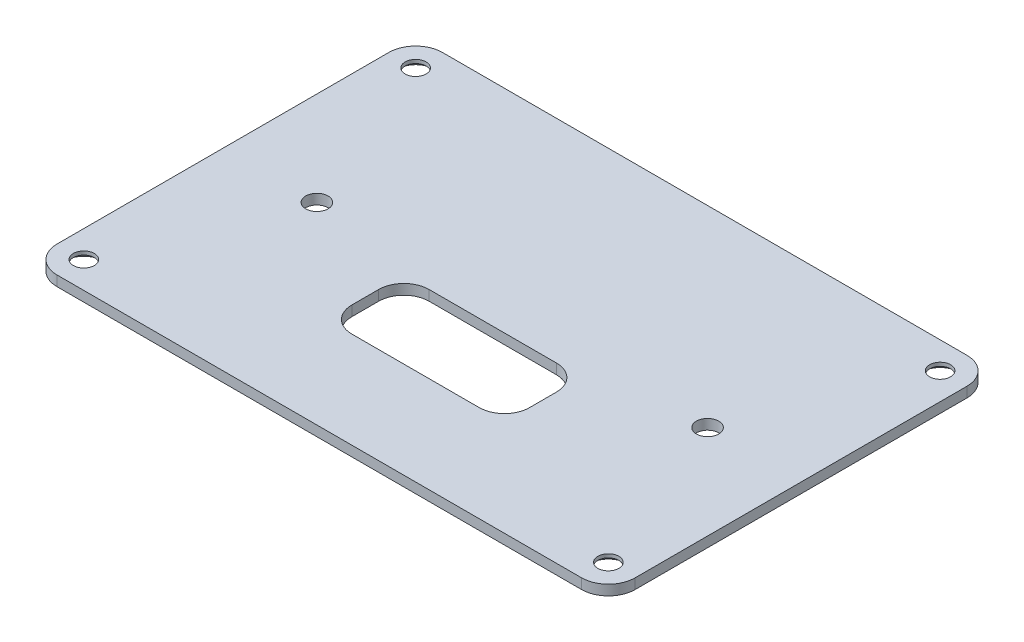
SolidWorks part; units mm, degrees
material "Plain Carbon Steel"
ref_plane "Front" through (0, 0, 0) normal (0, 0, 1) x (1, 0, 0)
ref_plane "Top" through (0, 0, 0) normal (0, 1, 0) x (1, 0, 0)
ref_plane "Right" through (0, 0, 0) normal (1, 0, 0) x (0, 0, -1)
sketch "Sketch1" plane through (0, 0, 0) normal (0, 1, 0) x (1, 0, 0)
  line L0 (-45, 0) -> (45, 0) construction
  line L1 (-45, 30) -> (45, 30) construction
  line L2 (-45, 30) -> (-45, -30) construction
  line L3 (-45, -30) -> (45, -30) construction
  line L4 (45, 30) -> (45, -30) construction
  line L5 (0, -30) -> (0, 30) construction
  line L6 (41.825, 26.825) -> (41.825, -26.825) construction
  line L7 (-41.825, -26.825) -> (41.825, -26.825) construction
  line L8 (-41.825, 26.825) -> (-41.825, -26.825) construction
  line L9 (-41.825, 26.825) -> (41.825, 26.825) construction
  line L10 (40.825, 25.825) -> (40.825, -25.825) construction
  line L11 (-40.825, -25.825) -> (40.825, -25.825) construction
  line L12 (-40.825, 25.825) -> (-40.825, -25.825) construction
  line L13 (-40.825, 25.825) -> (40.825, 25.825) construction
  line L14 (40.825, 21.65) -> (45, 21.65) construction
  line L15 (40.825, -21.65) -> (45, -21.65) construction
  line L16 (36.65, -25.825) -> (36.65, -30) construction
  line L17 (-36.65, -25.825) -> (-36.65, -30) construction
  line L18 (-40.825, -21.65) -> (-45, -21.65) construction
  line L19 (-36.65, 25.825) -> (-36.65, 30) construction
  line L20 (-40.825, 21.65) -> (-45, 21.65) construction
  line L21 (36.65, 25.825) -> (36.65, 30) construction
  line L22 (40.825, -25.825) -> (41.825, -25.825) construction
  circle A0 centre (-40.825, -25.825) radius 1 construction
  circle A1 centre (40.825, -25.825) radius 1 construction
  circle A2 centre (40.825, 25.825) radius 1 construction
  circle A3 centre (-40.825, 25.825) radius 1 construction
  circle A4 centre (40.825, -25.825) radius 4.175 construction
  circle A5 centre (40.825, 25.825) radius 4.175 construction
  circle A6 centre (-40.825, 25.825) radius 4.175 construction
  circle A7 centre (-40.825, -25.825) radius 4.175 construction
  dimension "D1" = 90
  dimension "D2" = 60
  dimension "D4" = 1
  dimension "D3" = 3.175
sketch "Sketch2" plane through (0, 0, 0) normal (0, 1, 0) x (1, 0, 0)
  line L0 (-45, 30) -> (-45, -30) construction
  line L1 (-45, -30) -> (45, -30) construction
  line L2 (45, 30) -> (45, -30) construction
  line L3 (-45, 30) -> (45, 30) construction
  line L16 (-45, 25.825) -> (-45, -25.825)
  line L17 (-40.825, -30) -> (40.825, -30)
  line L18 (45, 25.825) -> (45, -25.825)
  line L19 (-40.825, 30) -> (40.825, 30)
  circle A0 centre (40.825, 25.825) radius 4.175 construction
  circle A1 centre (40.825, 25.825) radius 1 construction
  circle A2 centre (-40.825, 25.825) radius 4.175 construction
  circle A3 centre (-40.825, 25.825) radius 1 construction
  arc A6 (45, 25.825) -> (40.825, 30) centre (40.825, 25.825) ccw
  circle A7 centre (40.825, 25.825) radius 1
  arc A8 (-40.825, 30) -> (-45, 25.825) centre (-40.825, 25.825) ccw
  circle A9 centre (-40.825, 25.825) radius 1
  circle A12 centre (-40.825, -25.825) radius 1 construction
  circle A13 centre (40.825, -25.825) radius 1 construction
  circle A14 centre (-40.825, -25.825) radius 1
  circle A15 centre (40.825, -25.825) radius 1
  arc A17 (-45, -25.825) -> (-40.825, -30) centre (-40.825, -25.825) ccw
  arc A18 (40.825, -30) -> (45, -25.825) centre (40.825, -25.825) ccw
extrude "Boss-Extrude3" add sketch "Sketch2" along normal blind 1.5875
sketch "Sketch4" plane through (0, 0, 0) normal (0, -1, 0) x (1, 0, 0)
  line L10 (-13.335, 6.9246) -> (-13.335, 11.0902) construction
  line L11 (-9.906, 14.5192) -> (9.906, 14.5192) construction
  line L12 (13.335, 6.9246) -> (13.335, 11.0902) construction
  line L13 (-9.906, 3.4956) -> (9.906, 3.4956) construction
  line L14 (-13.335, 6.9246) -> (-13.335, 11.0902) construction
  line L15 (-9.906, 14.5192) -> (9.906, 14.5192) construction
  line L16 (13.335, 6.9246) -> (13.335, 11.0902) construction
  line L17 (-9.906, 3.4956) -> (9.906, 3.4956) construction
  line L18 (-13.835, 6.9246) -> (-13.835, 11.0902)
  line L19 (-9.906, 15.0192) -> (9.906, 15.0192)
  line L20 (13.835, 6.9246) -> (13.835, 11.0902)
  line L21 (-9.906, 2.9956) -> (9.906, 2.9956)
  arc A4 (-9.906, 14.5192) -> (-13.335, 11.0902) centre (-9.906, 11.0902) ccw construction
  arc A5 (13.335, 11.0902) -> (9.906, 14.5192) centre (9.906, 11.0902) ccw construction
  arc A6 (9.906, 3.4956) -> (13.335, 6.9246) centre (9.906, 6.9246) ccw construction
  arc A7 (-13.335, 6.9246) -> (-9.906, 3.4956) centre (-9.906, 6.9246) ccw construction
  arc A8 (-9.906, 14.5192) -> (-13.335, 11.0902) centre (-9.906, 11.0902) ccw construction
  arc A9 (13.335, 11.0902) -> (9.906, 14.5192) centre (9.906, 11.0902) ccw construction
  arc A10 (9.906, 3.4956) -> (13.335, 6.9246) centre (9.906, 6.9246) ccw construction
  arc A11 (-13.335, 6.9246) -> (-9.906, 3.4956) centre (-9.906, 6.9246) ccw construction
  arc A12 (-9.906, 15.0192) -> (-13.835, 11.0902) centre (-9.906, 11.0902) ccw
  arc A13 (13.835, 11.0902) -> (9.906, 15.0192) centre (9.906, 11.0902) ccw
  arc A14 (9.906, 2.9956) -> (13.835, 6.9246) centre (9.906, 6.9246) ccw
  arc A15 (-13.835, 6.9246) -> (-9.906, 2.9956) centre (-9.906, 6.9246) ccw
  dimension "D1" = 0.5
extrude "DB15 Plug Cutaway" cut sketch "Sketch4" against normal through all
hole_wizard "CSK for #4 Flat Head Machine Screw (100)2" positions "Sketch10" profile "Sketch9" countersink size "#4" standard "ANSI Inch" end condition through all
sketch "Sketch10" plane through (0, 0, 0) normal (0, -1, 0) x (-1, 0, 0)
  point P0 (40.825, -25.825)
  point P5 (40.825, 25.825)
  point P9 (-40.825, -25.825)
  point P13 (-40.825, 25.825)
sketch "Sketch9" plane through (-40.825, 0, 25.825) normal (1, 0, 0) x (0, 0, -1)
  line L0 (0, 0) -> (0, 1.5875)
  line L1 (0, 1.5875) -> (1.6319, 1.5875)
  line L2 (1.6319, 1.5875) -> (1.6319, 1.0284)
  line L3 (1.6319, 1.0284) -> (2.8575, 0)
  line L5 (2.8575, 0) -> (0, 0)
  line L6 (-1.6319, 1.0284) -> (-2.8575, 0) construction
  line L11 (0, -6.35) -> (0, 107.95) construction
  dimension "Thru Hole Dia." = 3.2639
  dimension "Thru Hole Depth" = 1.5875
  dimension "Near C'Sink Dia." = 5.715
  dimension "Near C'Sink Angle" = 100
sketch "Sketch11" plane through (0, 0, 0) normal (0, -1, 0) x (1, 0, 0)
  line L0 (40.825, -25.825) -> (-40.825, -25.825) construction
  line L1 (-40.825, -25.825) -> (-40.825, 25.825) construction
  line L2 (-40.825, 25.825) -> (40.825, 25.684) construction
  line L3 (40.825, 25.684) -> (40.825, -25.825) construction
  line L4 (40.825, -0.0705) -> (-40.825, 0) construction
  line L5 (19.939, 9.0074) -> (40.825, 9.0074) construction
  line L6 (19.939, 13.935) -> (19.939, 4.0798) construction
  line L8 (-19.939, 9.0074) -> (-40.825, 9.0074) construction
  line L9 (-19.939, 13.935) -> (-19.939, 4.0798) construction
  line L10 (-30.382, 9.0074) -> (-30.382, -0.009) construction
  line L11 (30.382, 9.0074) -> (30.382, -0.0615) construction
  circle A0 centre (-30.382, -0.009) radius 1.7399
  circle A1 centre (30.382, -0.0615) radius 1.7399
  dimension "D1" = 3.4798
  dimension "D2" = 3.4798
extrude "Cut-Extrude1" cut sketch "Sketch11" against normal through all
